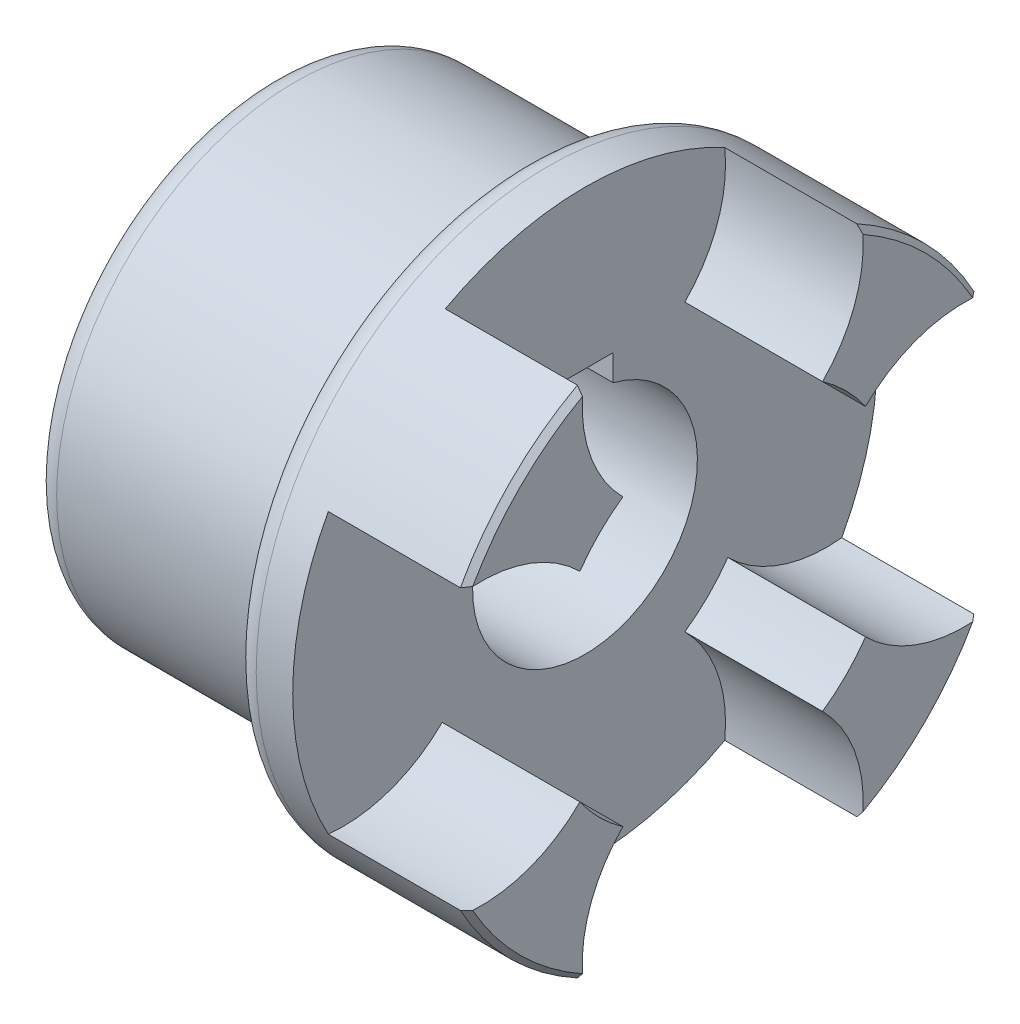
SolidWorks part; units mm, degrees
material "1.0037 (S235JR)"
ref_plane "Спереди" through (0, 0, 0) normal (0, 0, 1) x (1, 0, 0)
ref_plane "Сверху" through (0, 0, 0) normal (0, 1, 0) x (1, 0, 0)
ref_plane "Справа" through (0, 0, 0) normal (1, 0, 0) x (0, 0, -1)
sketch "Эскиз1" plane through (0, 0, 0) normal (0, 0, 1) x (1, 0, 0)
  line L0 (-70.2451, -27.6422) -> (10.2549, -27.6422) construction
  line L2 (-70.2451, -6.6422) -> (-69.2451, -7.6422)
  line L3 (-65.7451, 14.8578) -> (-29.7451, 14.8578)
  line L4 (-25.2451, 19.3578) -> (-25.2451, 19.8578)
  line L5 (10.2549, -6.6422) -> (10.2549, 23.3578)
  line L6 (-69.2451, -7.6422) -> (9.2549, -7.6422)
  line L7 (-20.7451, 24.3578) -> (9.2549, 24.3578)
  line L8 (9.2549, -7.6422) -> (10.2549, -6.6422)
  line L9 (10.2549, 23.3578) -> (9.2549, 24.3578)
  line L10 (-70.2451, 10.3578) -> (-70.2451, -6.6422)
  arc A0 (-20.7451, 24.3578) -> (-25.2451, 19.8578) centre (-20.7451, 19.8578) ccw
  arc A1 (-25.2451, 19.3578) -> (-29.7451, 14.8578) centre (-29.7451, 19.3578) cw
  arc A2 (-65.7451, 14.8578) -> (-70.2451, 10.3578) centre (-65.7451, 10.3578) ccw
  point P4 (-70.2451, -7.6422)
  point P8 (10.2549, 24.3578)
  point P9 (10.2549, -7.6422)
  dimension "D1" = 4.5
  dimension "D2" = 4.5
  dimension "D3" = 42.5
  dimension "D4" = 52
revolve "Повернуть1" add sketch "Эскиз1" angle 360 about L0
sketch "Эскиз3" plane through (10.2549, 0, 0) normal (1, 0, 0) x (0, 0, -1)
  circle A33 centre (0, -27.6422) radius 43 construction
  arc A35 (-17.7619, -53.0492) -> (17.7619, -53.0492) centre (0, -70.6422) ccw
  arc A36 (-25.407, -9.8803) -> (-25.407, -45.4041) centre (-43, -27.6422) ccw
  arc A37 (17.7619, -2.2352) -> (-17.7619, -2.2352) centre (0, 15.3578) ccw
  arc A38 (25.407, -45.4041) -> (25.407, -9.8803) centre (43, -27.6422) ccw
  arc A39 (17.7619, -53.0492) -> (25.407, -45.4041) centre (0, -27.6422) ccw
  arc A40 (-25.407, -45.4041) -> (-17.7619, -53.0492) centre (0, -27.6422) ccw
  arc A41 (-17.7619, -2.2352) -> (-25.407, -9.8803) centre (0, -27.6422) ccw
  arc A42 (25.407, -9.8803) -> (17.7619, -2.2352) centre (0, -27.6422) ccw
  dimension "D1" = 25
  dimension "D2" = 86
  dimension "D3" = 25
  dimension "D4" = 25
  dimension "D5" = 25
  dimension "D6" = 31
extrude "Вырез-Вытянуть1" cut sketch "Эскиз3" against normal blind 24.5
sketch "Эскиз4" plane through (-14.2451, 0, 0) normal (1, 0, 0) x (0, 0, -1)
  line L0 (-5, -14.0653) -> (5, -14.0653)
  line L1 (5, -14.0653) -> (5, -3.6422)
  line L2 (-5, -14.0653) -> (-5, -3.6422)
  line L3 (-5, -3.6422) -> (5, -3.6422)
extrude "Вырез-Вытянуть2" cut sketch "Эскиз4" against normal through all
